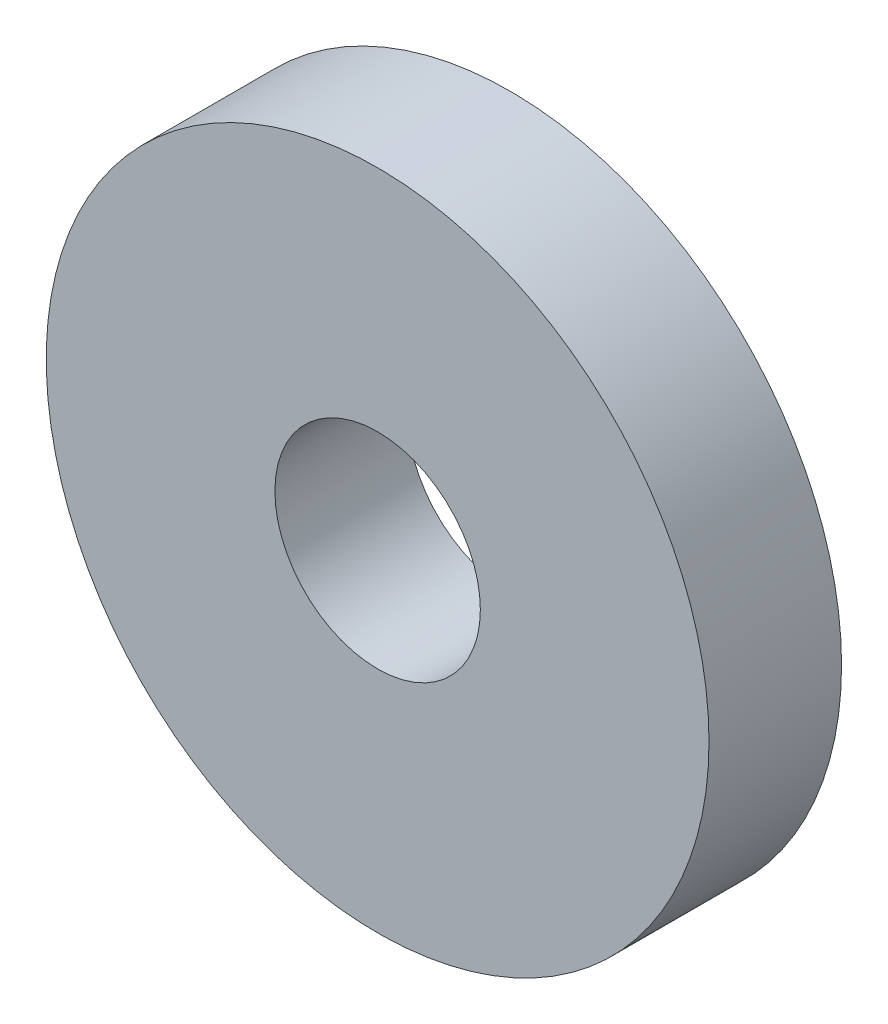
SolidWorks part; units mm, degrees
ref_plane "前视基准面" through (0, 0, 0) normal (0, 0, 1) x (1, 0, 0)
ref_plane "上视基准面" through (0, 0, 0) normal (0, 1, 0) x (1, 0, 0)
ref_plane "右视基准面" through (0, 0, 0) normal (1, 0, 0) x (0, 0, -1)
sketch "草图1" plane through (0, 0, 0) normal (0, 0, 1) x (1, 0, 0)
  circle A0 centre (0, 0) radius 25
extrude "凸台-拉伸1" add sketch "草图1" along normal blind 10
hole_wizard "M18 螺纹孔1" positions "草图7" profile "草图6" tap size "M18" standard "GB"
sketch "草图7" plane through (0, 0, 0) normal (0, 0, -1) x (-1, 0, 0)
  point P0 (0, 0)
sketch "草图6" plane through (0, 0, 0) normal (1, 0, 0) x (0, 1, 0)
  line L0 (0, 0) -> (0, 48.1567)
  line L1 (0, 48.1567) -> (7.75, 43.5)
  line L2 (7.75, 43.5) -> (7.75, 0)
  line L5 (7.75, 0) -> (0, 0)
  line L10 (0, 48.1567) -> (-7.75, 43.5) construction
  line L11 (0, -6.35) -> (0, 107.95) construction
  dimension "螺纹孔钻头直径" = 15.5
  dimension "螺纹孔钻头深度" = 43.5
  dimension "导头角度" = 118
cosmetic thread "孔螺蚊线2" parameters "D1"=10, "D2"=18
sketch "草图8" plane through (0, 0, 0) normal (0, 0, 1) x (1, 0, 0)
  circle A0 centre (0, 0) radius 18
  point P3 (18, 0)
  point P4 (0, 18)
  point P5 (-18, 0)
  point P6 (0, -18)
hole_wizard "M6 螺纹孔1" positions "草图10" profile "草图9" tap size "M6" standard "GB"
sketch "草图10" plane through (0, 0, 0) normal (0, 0, -1) x (-1, 0, 0)
  point P0 (0, 18)
  point P1 (-18, 0)
  point P3 (18, 0)
  point P5 (0, -18)
sketch "草图9" plane through (0, 18, 0) normal (1, 0, 0) x (0, 1, 0)
  line L0 (0, 0) -> (0, 6.5022)
  line L1 (0, 6.5022) -> (2.5, 5)
  line L2 (2.5, 5) -> (2.5, 0)
  line L5 (2.5, 0) -> (0, 0)
  line L10 (0, 6.5022) -> (-2.5, 5) construction
  line L11 (0, -6.35) -> (0, 107.95) construction
  dimension "螺纹孔钻头直径" = 5
  dimension "螺纹孔钻头深度" = 5
  dimension "导头角度" = 118
cosmetic thread "孔螺蚊线3" parameters "D1"=5, "D2"=6
cosmetic thread "孔螺蚊线4" parameters "D1"=5, "D2"=6
cosmetic thread "孔螺蚊线5" parameters "D1"=5, "D2"=6
cosmetic thread "孔螺蚊线6" parameters "D1"=5, "D2"=6
